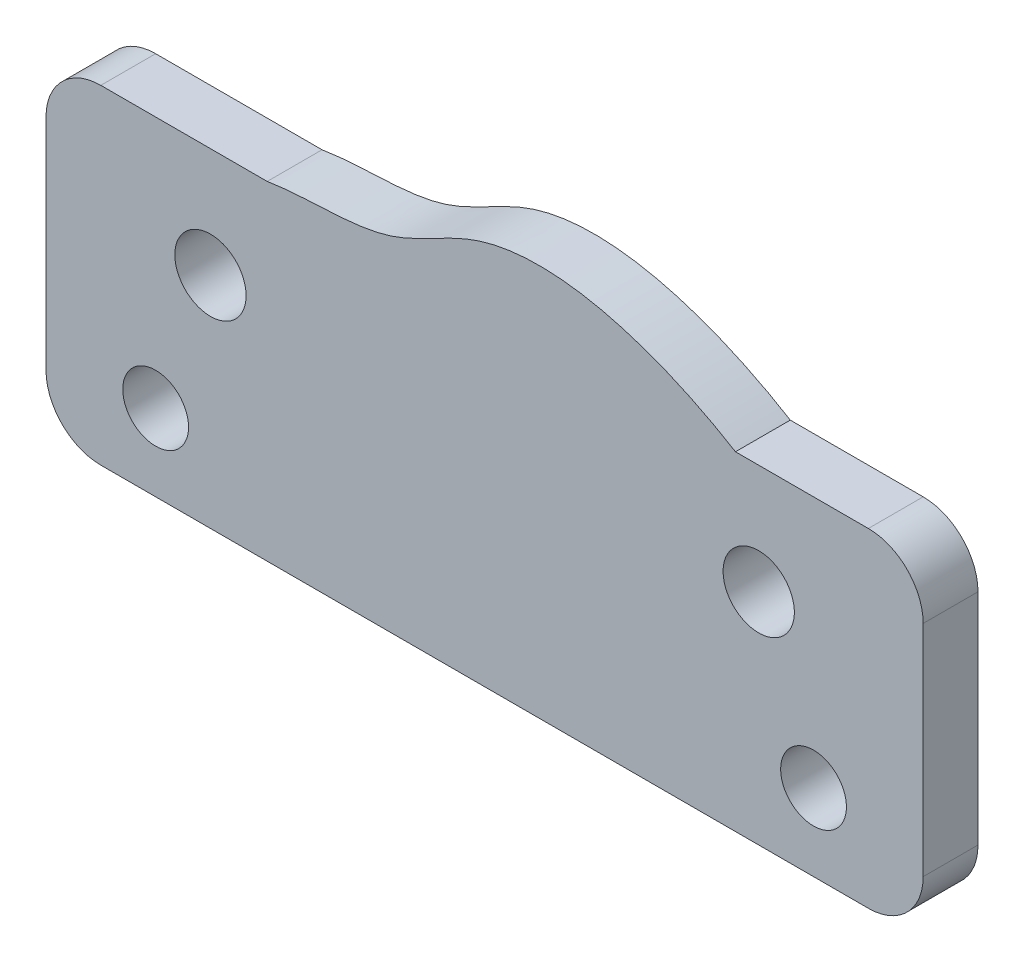
SolidWorks part; units mm, degrees
ref_plane "Front" through (0, 0, 0) normal (0, 0, 1) x (1, 0, 0)
ref_plane "Top" through (0, 0, 0) normal (0, 1, 0) x (1, 0, 0)
ref_plane "Right" through (0, 0, 0) normal (1, 0, 0) x (0, 0, -1)
sketch "Esquisse1" plane through (0, 0, 0) normal (0, 0, 1) x (1, 0, 0)
  line L1 (0, 0) -> (80, 0)
  line L2 (0, 0) -> (0, 30)
  line L3 (0, 30) -> (80, 30)
  line L4 (80, 0) -> (80, 30)
  dimension "D1" = 30
  dimension "D2" = 80
extrude "Boss.-Extru.1" add sketch "Esquisse1" along normal blind 5
sketch "Esquisse2" plane through (0, 0, 5) normal (0, 0, 1) x (1, 0, 0)
  line L0 (0, 20) -> (80, 20) construction
  line L1 (0, 30) -> (0, 0) construction
  line L2 (80, 0) -> (80, 30) construction
  line L3 (80, 30) -> (0, 30) construction
  line L4 (40, 20) -> (40, 30) construction
  line L5 (0, 10) -> (10, 10) construction
  circle A0 centre (15, 20) radius 3.25
  circle A1 centre (65, 20) radius 3.25
  circle A2 centre (10, 7) radius 3
  circle A3 centre (70, 7) radius 3
  dimension "D2" = 6.5
  dimension "D3" = 50
  dimension "D5" = 30
  dimension "D6" = 6
  dimension "D1" = 10
  dimension "D4" = 20
extrude "Enlèv. mat.-Extru.1" cut sketch "Esquisse2" against normal through all both and the other way through all
fillet "Congé1" radius 5 4 edges at (80, 0, 2.5) (80, 30, 2.5) (0, 30, 2.5) (0, 0, 2.5)
sketch "Esquisse3" plane through (0, 0, 5) normal (0, 0, 1) x (1, 0, 0)
  line L0 (75, 30) -> (5, 30) construction
  line L1 (20.1759, 30) -> (62.8804, 30)
  spline S0 degree 3 poles (62.8804, 30) (56.2486, 34.0442) (43.3425, 38.7775) (30.7539, 29.8552) (23.7569, 30.6156) (20.1759, 30) knots 0 0 0 0 0.562893 0.745093 1 1 1 1
extrude "Boss.-Extru.2" add sketch "Esquisse3" against normal up to vertex (5 mm away)
